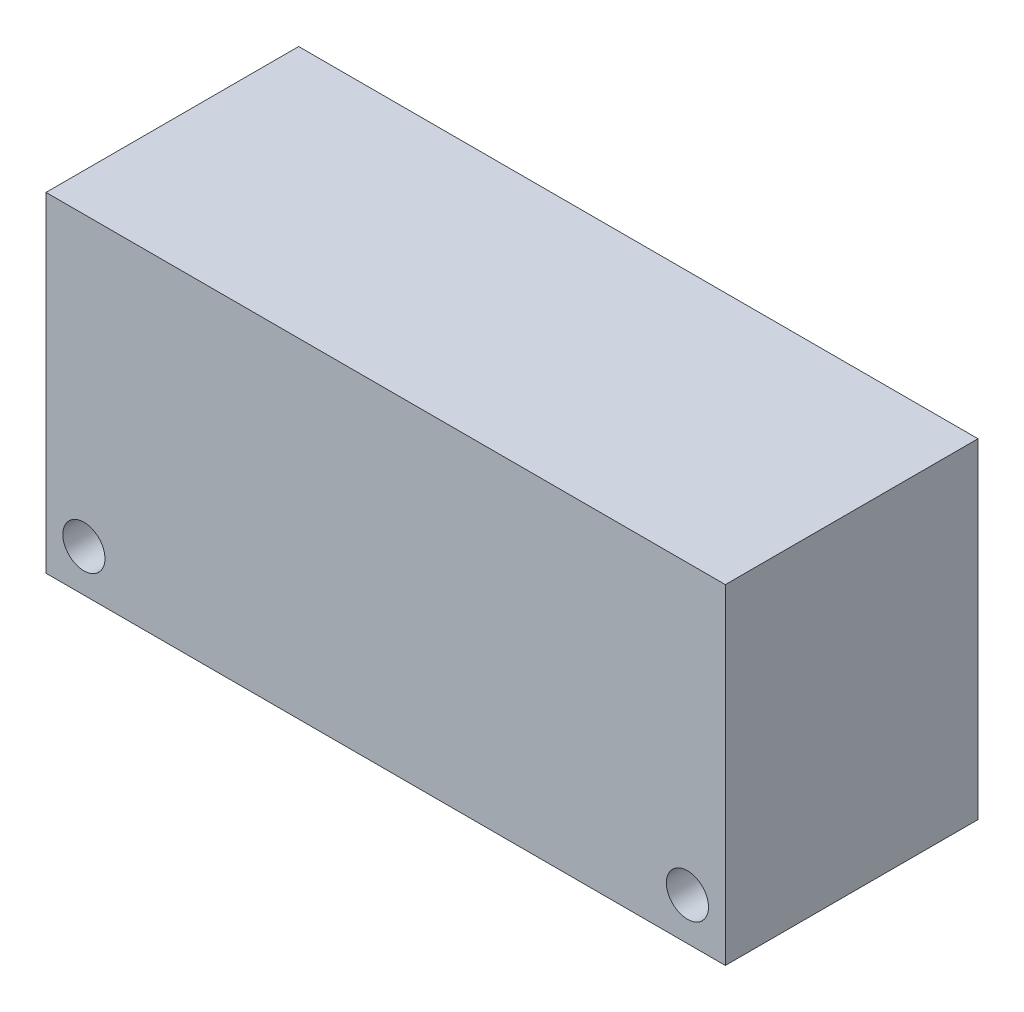
SolidWorks part; units mm, degrees
ref_plane "前基準面" through (0, 0, 0) normal (0, 0, 1) x (1, 0, 0)
ref_plane "上基準面" through (0, 0, 0) normal (0, 1, 0) x (1, 0, 0)
ref_plane "右基準面" through (0, 0, 0) normal (1, 0, 0) x (0, 0, -1)
sketch "草圖1" plane through (0, 0, 0) normal (0, 0, 1) x (1, 0, 0)
  line L0 (-21.5, -8.75) -> (21.5, -8.75) construction
  line L1 (-24.2, 11.75) -> (24.2, 11.75)
  line L2 (-24.2, 11.75) -> (-24.2, -11.75)
  line L3 (-24.2, -11.75) -> (24.2, -11.75)
  line L4 (24.2, 11.75) -> (24.2, -11.75)
  line L5 (-24.2, 11.75) -> (24.2, -11.75) construction
  line L6 (-24.2, -11.75) -> (24.2, 11.75) construction
  line L7 (0, -8.75) -> (0, 0) construction
  circle A0 centre (-21.5, -8.75) radius 1.5
  circle A1 centre (21.5, -8.75) radius 1.5
  point P0 (0, 0)
  dimension "D3" = 3
  dimension "D1" = 48.4
  dimension "D2" = 23.5
  dimension "D4" = 43
  dimension "D5" = 3
extrude "伸長1" add sketch "草圖1" along normal blind 18
